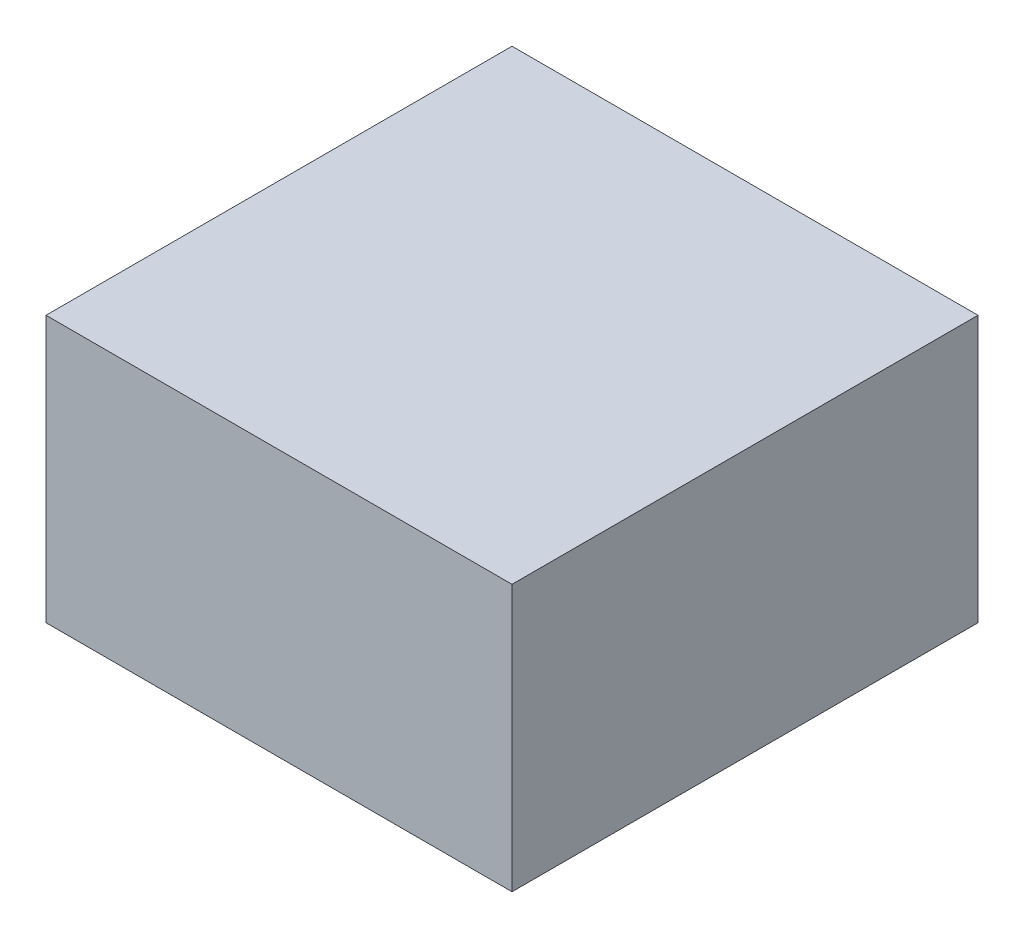
SolidWorks part; units mm, degrees
ref_plane "Front Plane" through (0, 0, 0) normal (0, 0, 1) x (1, 0, 0)
ref_plane "Top Plane" through (0, 0, 0) normal (0, 1, 0) x (1, 0, 0)
ref_plane "Right Plane" through (0, 0, 0) normal (1, 0, 0) x (0, 0, -1)
sketch "Sketch2" plane through (0, 0, 0) normal (0, 1, 0) x (1, 0, 0)
  line L1 (-88.9, 88.9) -> (88.9, 88.9)
  line L2 (-88.9, 88.9) -> (-88.9, -88.9)
  line L3 (-88.9, -88.9) -> (88.9, -88.9)
  line L4 (88.9, 88.9) -> (88.9, -88.9)
  line L5 (-88.9, 88.9) -> (88.9, -88.9) construction
  line L6 (-88.9, -88.9) -> (88.9, 88.9) construction
  point P0 (0, 0)
  dimension "D1" = 177.8
extrude "Boss-Extrude1" add sketch "Sketch2" along normal blind 101.6
